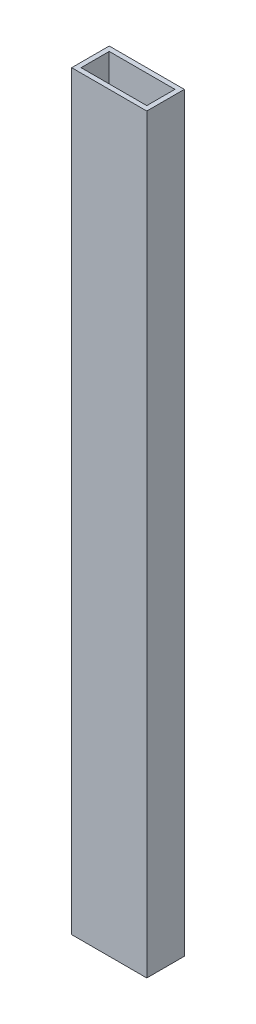
SolidWorks part; units mm, degrees
ref_plane "Front Plane" through (0, 0, 0) normal (0, 0, 1) x (1, 0, 0)
ref_plane "Top Plane" through (0, 0, 0) normal (0, 1, 0) x (1, 0, 0)
ref_plane "Right Plane" through (0, 0, 0) normal (1, 0, 0) x (0, 0, -1)
sketch "Sketch1" plane through (0, 0, 0) normal (0, 1, 0) x (1, 0, 0)
  line L0 (-22.225, 9.525) -> (22.225, 9.525)
  line L1 (-25.4, -12.7) -> (25.4, -12.7)
  line L2 (-25.4, -12.7) -> (-25.4, 12.7)
  line L3 (-25.4, 12.7) -> (25.4, 12.7)
  line L4 (25.4, -12.7) -> (25.4, 12.7)
  line L5 (-25.4, -12.7) -> (25.4, 12.7) construction
  line L6 (-25.4, 12.7) -> (25.4, -12.7) construction
  line L7 (22.225, -9.525) -> (22.225, 9.525)
  line L8 (-22.225, -9.525) -> (22.225, -9.525)
  line L9 (-22.225, -9.525) -> (-22.225, 9.525)
  point P0 (0, 0)
  dimension "D1" = 50.8
  dimension "D2" = 25.4
  dimension "D3" = 3.175
extrude "Boss-Extrude1" add sketch "Sketch1" along normal blind 508
